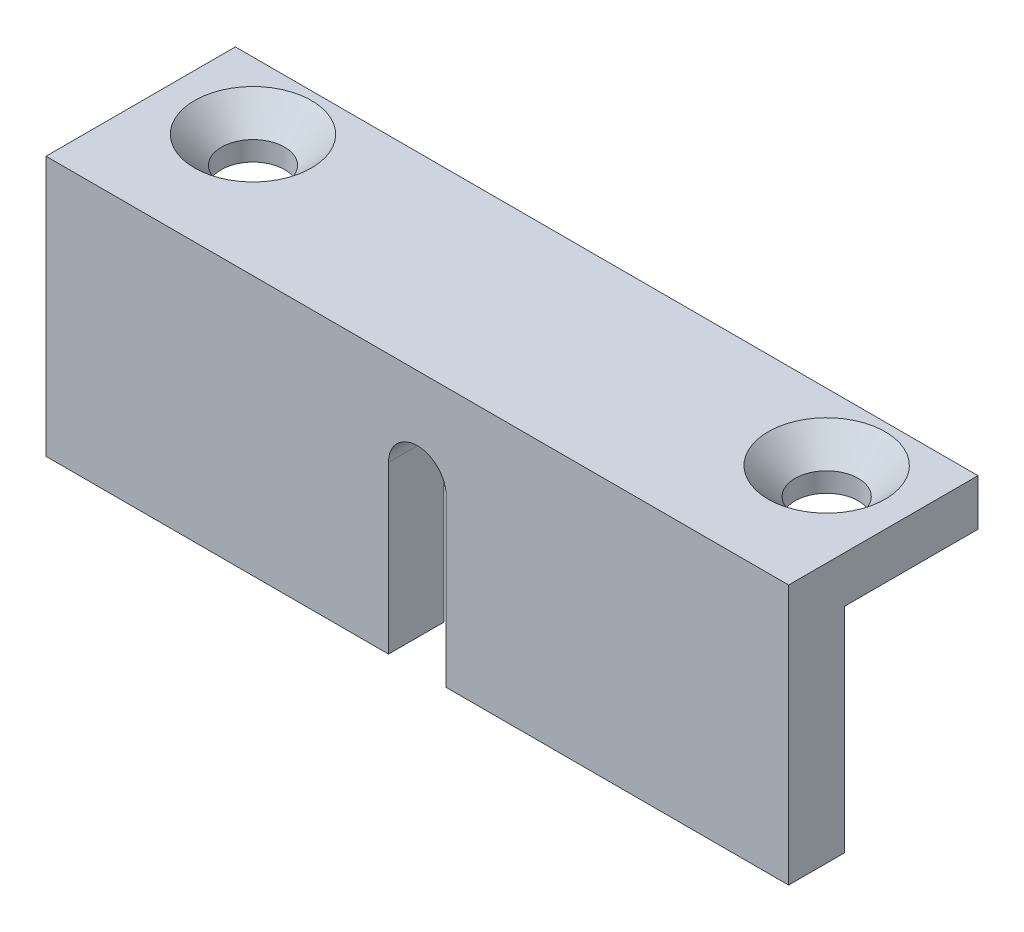
SolidWorks part; units mm, degrees
ref_plane "Front Plane" through (0, 0, 0) normal (0, 0, 1) x (1, 0, 0)
ref_plane "Top Plane" through (0, 0, 0) normal (0, 1, 0) x (1, 0, 0)
ref_plane "Right Plane" through (0, 0, 0) normal (1, 0, 0) x (0, 0, -1)
sketch "Sketch1" plane through (0, 0, 0) normal (0, 1, 0) x (1, 0, 0)
  line L0 (20, 7.2) -> (20, 0) construction
  line L1 (0, 0) -> (40, 0)
  line L2 (0, 0) -> (0, 7.2)
  line L3 (0, 7.2) -> (40, 7.2)
  line L4 (40, 0) -> (40, 7.2)
  point P5 (4.55, 3.6)
  point P9 (0, 3.6)
  point P10 (35.45, 3.6)
  dimension "D3" = 15.45
  dimension "D1" = 40
  dimension "D2" = 7.2
extrude "Boss-Extrude1" add sketch "Sketch1" along normal blind 2.5
sketch "Sketch2" plane through (0, 2.5, 0) normal (0, 1, 0) x (1, 0, 0)
  line L0 (20, 7.2) -> (20, 0) construction
  line L1 (0, 0) -> (40, 0)
  line L2 (0, 0) -> (0, 7.2)
  line L3 (0, 7.2) -> (40, 7.2)
  line L4 (40, 0) -> (40, 7.2)
  point P4 (4.55, 3.6)
  point P7 (0, 3.6)
  point P8 (35.45, 3.6)
  dimension "D1" = 7.2
  dimension "D2" = 40
  dimension "D3" = 4.55
hole_wizard "CSK for M3 Flat Head Machine Screw1" positions "Sketch2" profile "Sketch3" countersink size "M3" standard "ANSI Metric"
sketch "Sketch3" plane through (35.45, 2.5, -3.6) normal (1, 0, 0) x (0, 0, 1)
  line L0 (0, 0) -> (0, 2.5)
  line L1 (0, 2.5) -> (1.7, 2.5)
  line L2 (1.7, 2.5) -> (1.7, 1.45)
  line L3 (1.7, 1.45) -> (3.15, 0)
  line L5 (3.15, 0) -> (0, 0)
  line L6 (-1.7, 1.45) -> (-3.15, 0) construction
  line L11 (0, -6.35) -> (0, 107.95) construction
  dimension "Thru Hole Dia." = 3.4
  dimension "Thru Hole Depth" = 2.5
  dimension "Near C'Sink Dia." = 6.3
  dimension "Near C'Sink Angle" = 90
sketch "Sketch4" plane through (0, 2.5, 0) normal (0, 1, 0) x (1, 0, 0)
  line L0 (0, 0) -> (0, -3)
  line L1 (0, -3) -> (40, -3)
  line L2 (40, -3) -> (40, 0)
  line L3 (40, 0) -> (0, 0)
  dimension "D1" = 3
extrude "Boss-Extrude2" add sketch "Sketch4" against normal blind 14
sketch "Sketch5" plane through (0, 0, 3) normal (0, 0, 1) x (1, 0, 0)
  line L0 (20, -11.5) -> (20, -2.55) construction
  line L1 (0, -11.5) -> (40, -11.5) construction
  line L2 (18.45, -11.5) -> (18.45, -2.55)
  line L3 (21.55, -11.5) -> (21.55, -2.55)
  line L4 (18.45, -11.5) -> (21.55, -11.5)
  arc A0 (18.45, -11.5) -> (21.55, -11.5) centre (20, -11.5) ccw
  arc A1 (21.55, -2.55) -> (18.45, -2.55) centre (20, -2.55) ccw
  point P4 (20, -7.025)
  point P11 (20, -1)
  dimension "D1" = 3.1
  dimension "D2" = 10.5
extrude "Cut-Extrude1" cut sketch "Sketch5" against normal through all
